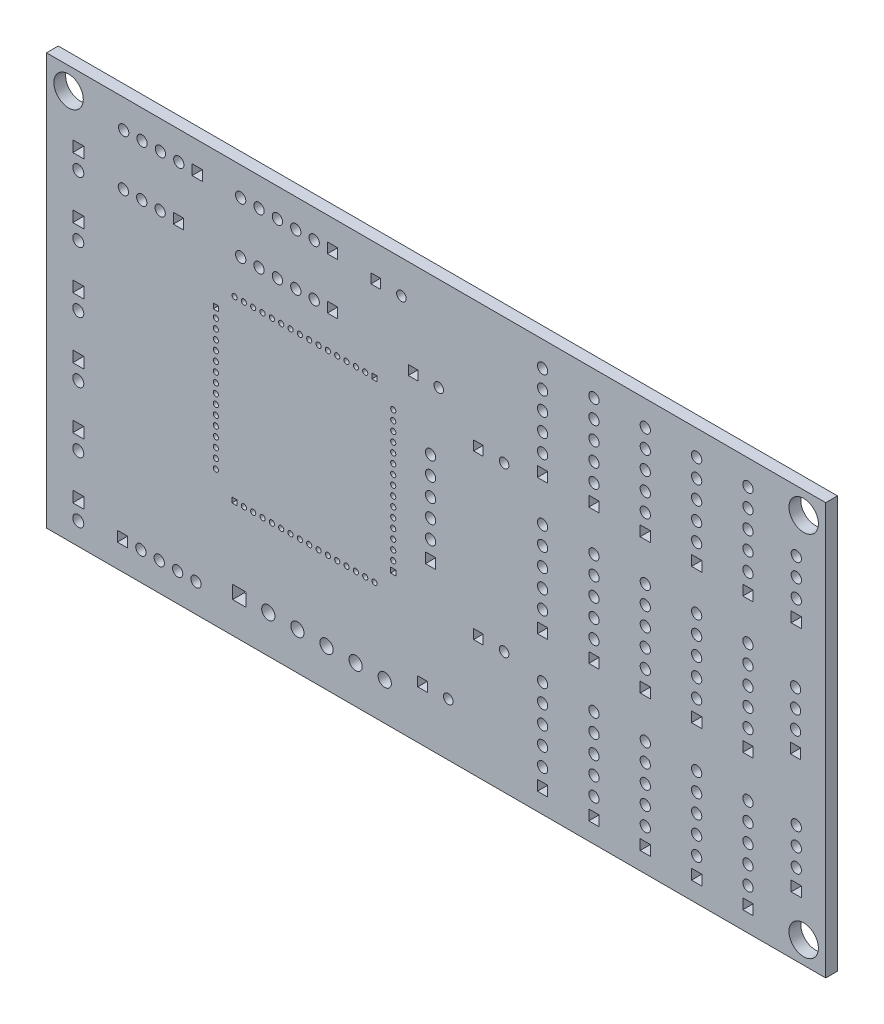
SolidWorks part; units mm, degrees
ref_plane "Front Plane" through (0, 0, 0) normal (0, 0, 1) x (1, 0, 0)
ref_plane "Top Plane" through (0, 0, 0) normal (0, 1, 0) x (1, 0, 0)
ref_plane "Right Plane" through (0, 0, 0) normal (1, 0, 0) x (0, 0, -1)
sketch "Model" plane through (0, 0, 0) normal (0, 0, 1) x (1, 0, 0)
  line L272 (22.685, 37.875) -> (23.385, 37.875)
  line L273 (23.385, 37.875) -> (23.385, 37.175)
  line L274 (23.385, 37.175) -> (22.685, 37.175)
  line L275 (22.685, 37.175) -> (22.685, 37.875)
  line L276 (25.225, 15.585) -> (25.225, 16.285)
  line L277 (25.225, 16.285) -> (25.925, 16.285)
  line L278 (25.925, 16.285) -> (25.925, 15.585)
  line L279 (25.925, 15.585) -> (25.225, 15.585)
  line L280 (47.515, 18.125) -> (46.815, 18.125)
  line L281 (46.815, 18.125) -> (46.815, 18.825)
  line L282 (46.815, 18.825) -> (47.515, 18.825)
  line L283 (47.515, 18.825) -> (47.515, 18.125)
  line L284 (44.975, 40.415) -> (44.975, 39.715)
  line L285 (44.975, 39.715) -> (44.275, 39.715)
  line L286 (44.275, 39.715) -> (44.275, 40.415)
  line L287 (44.275, 40.415) -> (44.975, 40.415)
  line L288 (3.57, 47.54) -> (5.07, 47.54)
  line L289 (5.07, 47.54) -> (5.07, 46.04)
  line L290 (5.07, 46.04) -> (3.57, 46.04)
  line L291 (3.57, 46.04) -> (3.57, 47.54)
  line L292 (3.57, 39.285) -> (5.07, 39.285)
  line L293 (5.07, 39.285) -> (5.07, 37.785)
  line L294 (5.07, 37.785) -> (3.57, 37.785)
  line L295 (3.57, 37.785) -> (3.57, 39.285)
  line L296 (3.57, 31.03) -> (5.07, 31.03)
  line L297 (5.07, 31.03) -> (5.07, 29.53)
  line L298 (5.07, 29.53) -> (3.57, 29.53)
  line L299 (3.57, 29.53) -> (3.57, 31.03)
  line L300 (3.57, 22.775) -> (5.07, 22.775)
  line L301 (5.07, 22.775) -> (5.07, 21.275)
  line L302 (5.07, 21.275) -> (3.57, 21.275)
  line L303 (3.57, 21.275) -> (3.57, 22.775)
  line L304 (3.57, 14.52) -> (5.07, 14.52)
  line L305 (5.07, 14.52) -> (5.07, 13.02)
  line L306 (5.07, 13.02) -> (3.57, 13.02)
  line L307 (3.57, 13.02) -> (3.57, 14.52)
  line L308 (3.57, 6.265) -> (5.07, 6.265)
  line L309 (5.07, 6.265) -> (5.07, 4.765)
  line L310 (5.07, 4.765) -> (3.57, 4.765)
  line L311 (3.57, 4.765) -> (3.57, 6.265)
  line L528 (25.31, 4.24) -> (25.31, 6.04)
  line L529 (25.31, 6.04) -> (27.11, 6.04)
  line L530 (27.11, 6.04) -> (27.11, 4.24)
  line L531 (27.11, 4.24) -> (25.31, 4.24)
  line L532 (68.185, 2.4) -> (66.785, 2.4)
  line L533 (66.785, 2.4) -> (66.785, 3.8)
  line L534 (66.785, 3.8) -> (68.185, 3.8)
  line L535 (68.185, 3.8) -> (68.185, 2.4)
  line L536 (75.17, 2.4) -> (73.77, 2.4)
  line L537 (73.77, 2.4) -> (73.77, 3.8)
  line L538 (73.77, 3.8) -> (75.17, 3.8)
  line L539 (75.17, 3.8) -> (75.17, 2.4)
  line L540 (82.155, 2.4) -> (80.755, 2.4)
  line L541 (80.755, 2.4) -> (80.755, 3.8)
  line L542 (80.755, 3.8) -> (82.155, 3.8)
  line L543 (82.155, 3.8) -> (82.155, 2.4)
  line L544 (89.14, 2.4) -> (87.74, 2.4)
  line L545 (87.74, 2.4) -> (87.74, 3.8)
  line L546 (87.74, 3.8) -> (89.14, 3.8)
  line L547 (89.14, 3.8) -> (89.14, 2.4)
  line L548 (96.125, 2.4) -> (94.725, 2.4)
  line L549 (94.725, 2.4) -> (94.725, 3.8)
  line L550 (94.725, 3.8) -> (96.125, 3.8)
  line L551 (96.125, 3.8) -> (96.125, 2.4)
  line L552 (68.185, 20.95) -> (66.785, 20.95)
  line L553 (66.785, 20.95) -> (66.785, 22.35)
  line L554 (66.785, 22.35) -> (68.185, 22.35)
  line L555 (68.185, 22.35) -> (68.185, 20.95)
  line L556 (75.17, 20.95) -> (73.77, 20.95)
  line L557 (73.77, 20.95) -> (73.77, 22.35)
  line L558 (73.77, 22.35) -> (75.17, 22.35)
  line L559 (75.17, 22.35) -> (75.17, 20.95)
  line L560 (82.155, 20.95) -> (80.755, 20.95)
  line L561 (80.755, 20.95) -> (80.755, 22.35)
  line L562 (80.755, 22.35) -> (82.155, 22.35)
  line L563 (82.155, 22.35) -> (82.155, 20.95)
  line L564 (89.14, 20.95) -> (87.74, 20.95)
  line L565 (87.74, 20.95) -> (87.74, 22.35)
  line L566 (87.74, 22.35) -> (89.14, 22.35)
  line L567 (89.14, 22.35) -> (89.14, 20.95)
  line L568 (96.125, 20.95) -> (94.725, 20.95)
  line L569 (94.725, 20.95) -> (94.725, 22.35)
  line L570 (94.725, 22.35) -> (96.125, 22.35)
  line L571 (96.125, 22.35) -> (96.125, 20.95)
  line L572 (68.185, 39.365) -> (66.785, 39.365)
  line L573 (66.785, 39.365) -> (66.785, 40.765)
  line L574 (66.785, 40.765) -> (68.185, 40.765)
  line L575 (68.185, 40.765) -> (68.185, 39.365)
  line L576 (75.17, 39.365) -> (73.77, 39.365)
  line L577 (73.77, 39.365) -> (73.77, 40.765)
  line L578 (73.77, 40.765) -> (75.17, 40.765)
  line L579 (75.17, 40.765) -> (75.17, 39.365)
  line L580 (82.155, 39.365) -> (80.755, 39.365)
  line L581 (80.755, 39.365) -> (80.755, 40.765)
  line L582 (80.755, 40.765) -> (82.155, 40.765)
  line L583 (82.155, 40.765) -> (82.155, 39.365)
  line L584 (89.14, 39.365) -> (87.74, 39.365)
  line L585 (87.74, 39.365) -> (87.74, 40.765)
  line L586 (87.74, 40.765) -> (89.14, 40.765)
  line L587 (89.14, 40.765) -> (89.14, 39.365)
  line L588 (96.125, 39.365) -> (94.725, 39.365)
  line L589 (94.725, 39.365) -> (94.725, 40.765)
  line L590 (94.725, 40.765) -> (96.125, 40.765)
  line L591 (96.125, 40.765) -> (96.125, 39.365)
  line L592 (39.61, 52.83) -> (39.61, 51.43)
  line L593 (39.61, 51.43) -> (38.21, 51.43)
  line L594 (38.21, 51.43) -> (38.21, 52.83)
  line L595 (38.21, 52.83) -> (39.61, 52.83)
  line L596 (39.61, 45.845) -> (39.61, 44.445)
  line L597 (39.61, 44.445) -> (38.21, 44.445)
  line L598 (38.21, 44.445) -> (38.21, 45.845)
  line L599 (38.21, 45.845) -> (39.61, 45.845)
  line L600 (52.945, 21.585) -> (51.545, 21.585)
  line L601 (51.545, 21.585) -> (51.545, 22.985)
  line L602 (51.545, 22.985) -> (52.945, 22.985)
  line L603 (52.945, 22.985) -> (52.945, 21.585)
  line L1084 (21.195, 52.83) -> (21.195, 51.43)
  line L1085 (21.195, 51.43) -> (19.795, 51.43)
  line L1086 (19.795, 51.43) -> (19.795, 52.83)
  line L1087 (19.795, 52.83) -> (21.195, 52.83)
  line L1088 (9.635, 3.17) -> (9.635, 4.57)
  line L1089 (9.635, 4.57) -> (11.035, 4.57)
  line L1090 (11.035, 4.57) -> (11.035, 3.17)
  line L1091 (11.035, 3.17) -> (9.635, 3.17)
  line L1092 (18.655, 45.845) -> (18.655, 44.445)
  line L1093 (18.655, 44.445) -> (17.255, 44.445)
  line L1094 (17.255, 44.445) -> (17.255, 45.845)
  line L1095 (17.255, 45.845) -> (18.655, 45.845)
  line L1096 (102.7, 39.5) -> (101.3, 39.5)
  line L1097 (101.3, 39.5) -> (101.3, 40.9)
  line L1098 (101.3, 40.9) -> (102.7, 40.9)
  line L1099 (102.7, 40.9) -> (102.7, 39.5)
  line L1100 (102.6, 24) -> (101.2, 24)
  line L1101 (101.2, 24) -> (101.2, 25.4)
  line L1102 (101.2, 25.4) -> (102.6, 25.4)
  line L1103 (102.6, 25.4) -> (102.6, 24)
  line L1104 (102.7, 7.8) -> (101.3, 7.8)
  line L1105 (101.3, 7.8) -> (101.3, 9.2)
  line L1106 (101.3, 9.2) -> (102.7, 9.2)
  line L1107 (102.7, 9.2) -> (102.7, 7.8)
  line L1108 (50.5, 6.55) -> (50.5, 7.85)
  line L1109 (50.5, 7.85) -> (51.8, 7.85)
  line L1110 (51.8, 7.85) -> (51.8, 6.55)
  line L1111 (51.8, 6.55) -> (50.5, 6.55)
  line L1112 (58.1, 15.92) -> (58.1, 17.22)
  line L1113 (58.1, 17.22) -> (59.4, 17.22)
  line L1114 (59.4, 17.22) -> (59.4, 15.92)
  line L1115 (59.4, 15.92) -> (58.1, 15.92)
  line L1116 (58.1, 38.145) -> (58.1, 39.445)
  line L1117 (58.1, 39.445) -> (59.4, 39.445)
  line L1118 (59.4, 39.445) -> (59.4, 38.145)
  line L1119 (59.4, 38.145) -> (58.1, 38.145)
  line L1120 (44.13, 50.845) -> (44.13, 52.145)
  line L1121 (44.13, 52.145) -> (45.43, 52.145)
  line L1122 (45.43, 52.145) -> (45.43, 50.845)
  line L1123 (45.43, 50.845) -> (44.13, 50.845)
  line L1124 (49.21, 42.59) -> (49.21, 43.89)
  line L1125 (49.21, 43.89) -> (50.51, 43.89)
  line L1126 (50.51, 43.89) -> (50.51, 42.59)
  line L1127 (50.51, 42.59) -> (49.21, 42.59)
  line L1128 (0, 0) -> (0, 56)
  line L1129 (0, 56) -> (106, 56)
  line L1130 (106, 56) -> (106, 0)
  line L1131 (106, 0) -> (0, 0)
  circle A0 centre (23.035, 36.255) radius 0.35
  circle A1 centre (23.035, 34.985) radius 0.35
  circle A2 centre (23.035, 33.715) radius 0.35
  circle A3 centre (23.035, 32.445) radius 0.35
  circle A4 centre (23.035, 31.175) radius 0.35
  circle A5 centre (23.035, 29.905) radius 0.35
  circle A6 centre (23.035, 28.635) radius 0.35
  circle A7 centre (23.035, 27.365) radius 0.35
  circle A8 centre (23.035, 26.095) radius 0.35
  circle A9 centre (23.035, 24.825) radius 0.35
  circle A10 centre (23.035, 23.555) radius 0.35
  circle A11 centre (23.035, 22.285) radius 0.35
  circle A12 centre (23.035, 21.015) radius 0.35
  circle A13 centre (23.035, 19.745) radius 0.35
  circle A14 centre (23.035, 18.475) radius 0.35
  circle A15 centre (26.845, 15.935) radius 0.35
  circle A16 centre (28.115, 15.935) radius 0.35
  circle A17 centre (29.385, 15.935) radius 0.35
  circle A18 centre (30.655, 15.935) radius 0.35
  circle A19 centre (31.925, 15.935) radius 0.35
  circle A20 centre (33.195, 15.935) radius 0.35
  circle A21 centre (34.465, 15.935) radius 0.35
  circle A22 centre (35.735, 15.935) radius 0.35
  circle A23 centre (37.005, 15.935) radius 0.35
  circle A24 centre (38.275, 15.935) radius 0.35
  circle A25 centre (39.545, 15.935) radius 0.35
  circle A26 centre (40.815, 15.935) radius 0.35
  circle A27 centre (42.085, 15.935) radius 0.35
  circle A28 centre (43.355, 15.935) radius 0.35
  circle A29 centre (44.625, 15.935) radius 0.35
  circle A30 centre (47.165, 19.745) radius 0.35
  circle A31 centre (47.165, 21.015) radius 0.35
  circle A32 centre (47.165, 22.285) radius 0.35
  circle A33 centre (47.165, 23.555) radius 0.35
  circle A34 centre (47.165, 24.825) radius 0.35
  circle A35 centre (47.165, 26.095) radius 0.35
  circle A36 centre (47.165, 27.365) radius 0.35
  circle A37 centre (47.165, 28.635) radius 0.35
  circle A38 centre (47.165, 29.905) radius 0.35
  circle A39 centre (47.165, 31.175) radius 0.35
  circle A40 centre (47.165, 32.445) radius 0.35
  circle A41 centre (47.165, 33.715) radius 0.35
  circle A42 centre (47.165, 34.985) radius 0.35
  circle A43 centre (47.165, 36.255) radius 0.35
  circle A44 centre (47.165, 37.525) radius 0.35
  circle A45 centre (43.355, 40.065) radius 0.35
  circle A46 centre (42.085, 40.065) radius 0.35
  circle A47 centre (40.815, 40.065) radius 0.35
  circle A48 centre (39.545, 40.065) radius 0.35
  circle A49 centre (38.275, 40.065) radius 0.35
  circle A50 centre (37.005, 40.065) radius 0.35
  circle A51 centre (35.735, 40.065) radius 0.35
  circle A52 centre (34.465, 40.065) radius 0.35
  circle A53 centre (33.195, 40.065) radius 0.35
  circle A54 centre (31.925, 40.065) radius 0.35
  circle A55 centre (30.655, 40.065) radius 0.35
  circle A56 centre (29.385, 40.065) radius 0.35
  circle A57 centre (28.115, 40.065) radius 0.35
  circle A58 centre (26.845, 40.065) radius 0.35
  circle A59 centre (25.575, 40.065) radius 0.35
  circle A60 centre (4.32, 44.29) radius 0.75
  circle A61 centre (4.32, 36.035) radius 0.75
  circle A62 centre (4.32, 27.78) radius 0.75
  circle A63 centre (4.32, 19.525) radius 0.75
  circle A64 centre (4.32, 11.27) radius 0.75
  circle A65 centre (4.32, 3.015) radius 0.75
  circle A66 centre (30.17, 5.14) radius 0.9
  circle A67 centre (34.13, 5.14) radius 0.9
  circle A68 centre (38.09, 5.14) radius 0.9
  circle A69 centre (42.05, 5.14) radius 0.9
  circle A70 centre (46.01, 5.14) radius 0.9
  circle A71 centre (67.485, 5.6) radius 0.7
  circle A72 centre (67.485, 8.1) radius 0.7
  circle A73 centre (67.485, 10.6) radius 0.7
  circle A74 centre (67.485, 13.1) radius 0.7
  circle A75 centre (67.485, 15.6) radius 0.7
  circle A76 centre (74.47, 5.6) radius 0.7
  circle A77 centre (74.47, 8.1) radius 0.7
  circle A78 centre (74.47, 10.6) radius 0.7
  circle A79 centre (74.47, 13.1) radius 0.7
  circle A80 centre (74.47, 15.6) radius 0.7
  circle A81 centre (81.455, 5.6) radius 0.7
  circle A82 centre (81.455, 8.1) radius 0.7
  circle A83 centre (81.455, 10.6) radius 0.7
  circle A84 centre (81.455, 13.1) radius 0.7
  circle A85 centre (81.455, 15.6) radius 0.7
  circle A86 centre (88.44, 5.6) radius 0.7
  circle A87 centre (88.44, 8.1) radius 0.7
  circle A88 centre (88.44, 10.6) radius 0.7
  circle A89 centre (88.44, 13.1) radius 0.7
  circle A90 centre (88.44, 15.6) radius 0.7
  circle A91 centre (95.425, 5.6) radius 0.7
  circle A92 centre (95.425, 8.1) radius 0.7
  circle A93 centre (95.425, 10.6) radius 0.7
  circle A94 centre (95.425, 13.1) radius 0.7
  circle A95 centre (95.425, 15.6) radius 0.7
  circle A96 centre (67.485, 24.15) radius 0.7
  circle A97 centre (67.485, 26.65) radius 0.7
  circle A98 centre (67.485, 29.15) radius 0.7
  circle A99 centre (67.485, 31.65) radius 0.7
  circle A100 centre (67.485, 34.15) radius 0.7
  circle A101 centre (74.47, 24.15) radius 0.7
  circle A102 centre (74.47, 26.65) radius 0.7
  circle A103 centre (74.47, 29.15) radius 0.7
  circle A104 centre (74.47, 31.65) radius 0.7
  circle A105 centre (74.47, 34.15) radius 0.7
  circle A106 centre (81.455, 24.15) radius 0.7
  circle A107 centre (81.455, 26.65) radius 0.7
  circle A108 centre (81.455, 29.15) radius 0.7
  circle A109 centre (81.455, 31.65) radius 0.7
  circle A110 centre (81.455, 34.15) radius 0.7
  circle A111 centre (88.44, 24.15) radius 0.7
  circle A112 centre (88.44, 26.65) radius 0.7
  circle A113 centre (88.44, 29.15) radius 0.7
  circle A114 centre (88.44, 31.65) radius 0.7
  circle A115 centre (88.44, 34.15) radius 0.7
  circle A116 centre (95.425, 24.15) radius 0.7
  circle A117 centre (95.425, 26.65) radius 0.7
  circle A118 centre (95.425, 29.15) radius 0.7
  circle A119 centre (95.425, 31.65) radius 0.7
  circle A120 centre (95.425, 34.15) radius 0.7
  circle A121 centre (67.485, 42.565) radius 0.7
  circle A122 centre (67.485, 45.065) radius 0.7
  circle A123 centre (67.485, 47.565) radius 0.7
  circle A124 centre (67.485, 50.065) radius 0.7
  circle A125 centre (67.485, 52.565) radius 0.7
  circle A126 centre (74.47, 42.565) radius 0.7
  circle A127 centre (74.47, 45.065) radius 0.7
  circle A128 centre (74.47, 47.565) radius 0.7
  circle A129 centre (74.47, 50.065) radius 0.7
  circle A130 centre (74.47, 52.565) radius 0.7
  circle A131 centre (81.455, 42.565) radius 0.7
  circle A132 centre (81.455, 45.065) radius 0.7
  circle A133 centre (81.455, 47.565) radius 0.7
  circle A134 centre (81.455, 50.065) radius 0.7
  circle A135 centre (81.455, 52.565) radius 0.7
  circle A136 centre (88.44, 42.565) radius 0.7
  circle A137 centre (88.44, 45.065) radius 0.7
  circle A138 centre (88.44, 47.565) radius 0.7
  circle A139 centre (88.44, 50.065) radius 0.7
  circle A140 centre (88.44, 52.565) radius 0.7
  circle A141 centre (95.425, 42.565) radius 0.7
  circle A142 centre (95.425, 45.065) radius 0.7
  circle A143 centre (95.425, 47.565) radius 0.7
  circle A144 centre (95.425, 50.065) radius 0.7
  circle A145 centre (95.425, 52.565) radius 0.7
  circle A146 centre (36.41, 52.13) radius 0.7
  circle A147 centre (33.91, 52.13) radius 0.7
  circle A148 centre (31.41, 52.13) radius 0.7
  circle A149 centre (28.91, 52.13) radius 0.7
  circle A150 centre (26.41, 52.13) radius 0.7
  circle A151 centre (36.41, 45.145) radius 0.7
  circle A152 centre (33.91, 45.145) radius 0.7
  circle A153 centre (31.41, 45.145) radius 0.7
  circle A154 centre (28.91, 45.145) radius 0.7
  circle A155 centre (26.41, 45.145) radius 0.7
  circle A156 centre (52.245, 24.785) radius 0.7
  circle A157 centre (52.245, 27.285) radius 0.7
  circle A158 centre (52.245, 29.785) radius 0.7
  circle A159 centre (52.245, 32.285) radius 0.7
  circle A160 centre (52.245, 34.785) radius 0.7
  circle A161 centre (17.995, 52.13) radius 0.7
  circle A162 centre (15.495, 52.13) radius 0.7
  circle A163 centre (12.995, 52.13) radius 0.7
  circle A164 centre (10.495, 52.13) radius 0.7
  circle A165 centre (12.835, 3.87) radius 0.7
  circle A166 centre (15.335, 3.87) radius 0.7
  circle A167 centre (17.835, 3.87) radius 0.7
  circle A168 centre (20.335, 3.87) radius 0.7
  circle A169 centre (15.455, 45.145) radius 0.7
  circle A170 centre (12.955, 45.145) radius 0.7
  circle A171 centre (10.455, 45.145) radius 0.7
  circle A172 centre (102, 42.7) radius 0.7
  circle A173 centre (102, 45.2) radius 0.7
  circle A174 centre (102, 47.7) radius 0.7
  circle A175 centre (101.9, 27.2) radius 0.7
  circle A176 centre (101.9, 29.7) radius 0.7
  circle A177 centre (101.9, 32.2) radius 0.7
  circle A178 centre (102, 11) radius 0.7
  circle A179 centre (102, 13.5) radius 0.7
  circle A180 centre (102, 16) radius 0.7
  circle A181 centre (54.65, 7.2) radius 0.65
  circle A182 centre (62.25, 16.57) radius 0.65
  circle A183 centre (62.25, 38.795) radius 0.65
  circle A184 centre (48.28, 51.495) radius 0.65
  circle A185 centre (53.36, 43.24) radius 0.65
  circle A186 centre (3, 53) radius 2
  circle A187 centre (103, 3) radius 2
  circle A188 centre (103, 53) radius 2
extrude "Boss-Extrude1" add sketch "Model" along normal blind 1.6
